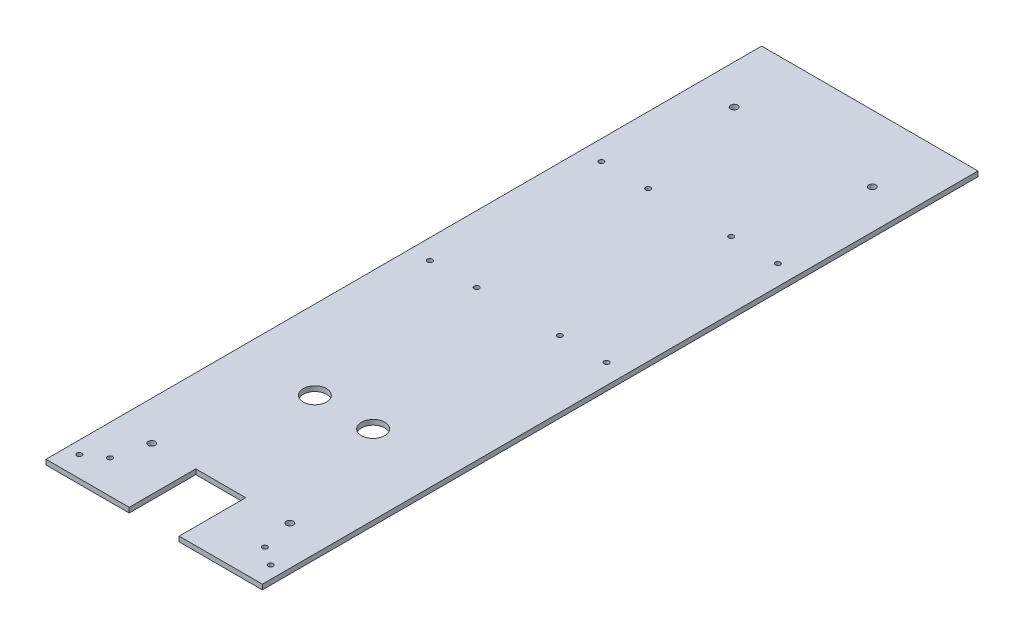
SolidWorks part; units mm, degrees
ref_plane "Front Plane" through (0, 0, 0) normal (0, 0, 1) x (1, 0, 0)
ref_plane "Top Plane" through (0, 0, 0) normal (0, 1, 0) x (1, 0, 0)
ref_plane "Right Plane" through (0, 0, 0) normal (1, 0, 0) x (0, 0, -1)
sketch "Sketch1" plane through (0, 0, 0) normal (0, 1, 0) x (1, 0, 0)
  line L1 (-65, 215) -> (65, 215)
  line L2 (-65, 215) -> (-65, -215)
  line L3 (-65, -215) -> (65, -215)
  line L4 (65, 215) -> (65, -215)
  line L5 (-65, 215) -> (65, -215) construction
  line L6 (-65, -215) -> (65, 215) construction
  point P0 (0, 0)
  dimension "D1" = 130
  dimension "D2" = 430
extrude "Boss-Extrude1" add sketch "Sketch1" along normal blind 3
sketch "Sketch2" plane through (0, 3, 0) normal (0, 1, 0) x (1, 0, 0)
  line L0 (-65, -215) -> (65, -215) construction
  line L1 (15, -215) -> (-15, -215)
  line L2 (15, -215) -> (15, -175)
  line L3 (15, -175) -> (-15, -175)
  line L4 (-15, -215) -> (-15, -175)
  line L5 (33, -215) -> (33, 215) construction
  line L6 (-33, -215) -> (-33, 215) construction
  dimension "D3" = 0
  dimension "D1" = 18
  dimension "D2" = 18
  dimension "D4" = 40
extrude "Cut-Extrude1" cut sketch "Sketch2" against normal blind 10 contours L2 L3 L4 L1
sketch "Sketch3" plane through (0, 0, 0) normal (0, -1, 0) x (1, 0, 0)
  line L0 (0, 33.6472) -> (0, -145.4342) construction
  line L1 (-65, -215) -> (-65, 215) construction
  circle A0 centre (-53.05, -3.75) radius 1.5
  circle A1 centre (-46.5, 195) radius 1.5
  circle A2 centre (-24.95, -3.75) radius 1.5
  circle A3 centre (-53.05, -106.75) radius 1.5
  circle A4 centre (46.5, 195) radius 1.5
  circle A5 centre (-24.95, -106.75) radius 1.5
  circle A6 centre (24.95, -106.75) radius 1.5
  circle A7 centre (57.5, 202.5) radius 1.5
  circle A8 centre (53.05, -106.75) radius 1.5
  circle A9 centre (24.95, -3.75) radius 1.5
  circle A10 centre (-57.5, 202.5) radius 1.5
  circle A11 centre (53.05, -3.75) radius 1.5
  circle A12 centre (-41.5, 175) radius 2.1
  circle A13 centre (41.5, 175) radius 2.1
  circle A14 centre (41.5, -175) radius 2.1
  circle A15 centre (-41.5, -175) radius 2.1
  dimension "D1" = 3
  dimension "D3" = 3
  dimension "D4" = 3
  dimension "D5" = 4.2
  dimension "D2" = 65
extrude "Cut-Extrude2" cut sketch "Sketch3" against normal blind 10
sketch "Sketch4" plane through (0, 0, 0) normal (0, -1, 0) x (1, 0, 0)
  line L0 (-65, -215) -> (-65, 215) construction
  circle A0 centre (-17.5, 100.9522) radius 7
  circle A1 centre (17.5, 100.9522) radius 7
  dimension "D1" = 35
  dimension "D2" = 47.5
  dimension "D3" = 14
  dimension "D4" = 14
extrude "Cut-Extrude3" cut sketch "Sketch4" against normal blind 10
